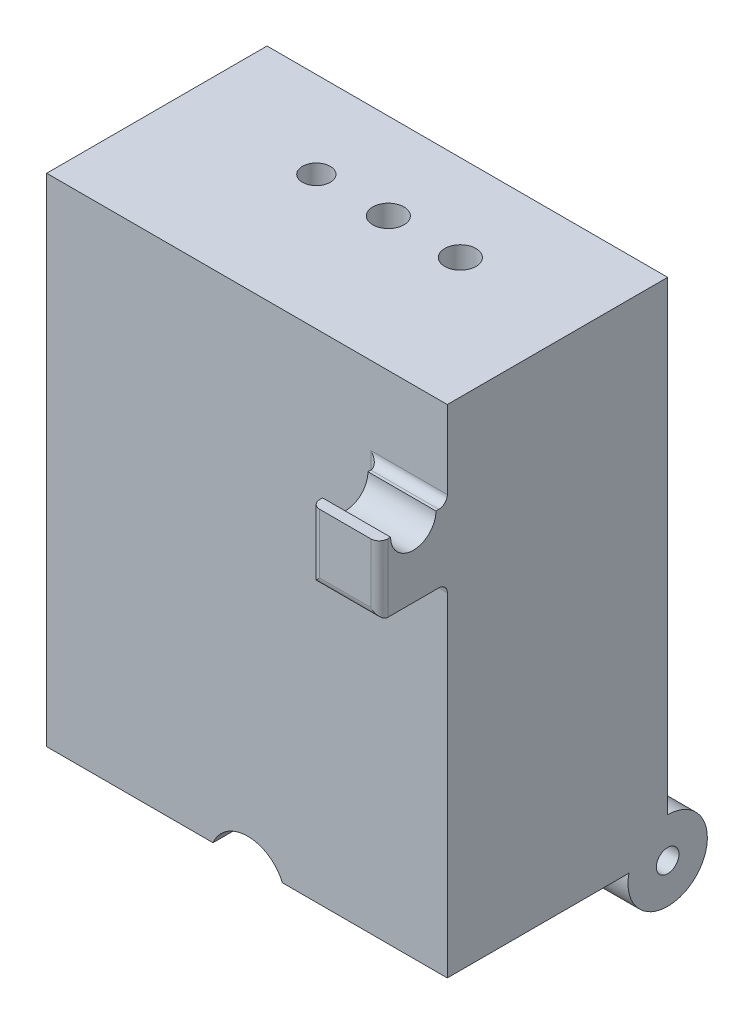
SolidWorks part; units mm, degrees
ref_plane "Front Plane" through (0, 0, 0) normal (0, 0, 1) x (1, 0, 0)
ref_plane "Top Plane" through (0, 0, 0) normal (0, 1, 0) x (1, 0, 0)
ref_plane "Right Plane" through (0, 0, 0) normal (1, 0, 0) x (0, 0, -1)
sketch "Sketch1" plane through (0, 0, 0) normal (1, 0, 0) x (0, 0, -1)
  line L1 (-15.935, -35.8) -> (15.935, -35.8)
  line L2 (-15.935, -35.8) -> (-15.935, 35.8)
  line L3 (-15.935, 35.8) -> (15.935, 35.8)
  line L4 (15.935, -35.8) -> (15.935, 35.8)
  line L5 (-15.935, -35.8) -> (15.935, 35.8) construction
  line L6 (-15.935, 35.8) -> (15.935, -35.8) construction
  point P0 (0, 0)
extrude "Boss-Extrude1" add sketch "Sketch1" along normal blind 56.17
sketch "Sketch2" plane through (0, 0, -15.935) normal (0, 0, -1) x (-1, 0, 0)
  line L4 (-56.17, 35.8) -> (-56.17, -35.8)
  line L5 (-56.17, -35.8) -> (0, -35.8)
  line L6 (0, -35.8) -> (0, 35.8)
  line L7 (0, 35.8) -> (-56.17, 35.8)
  line L8 (8, -43.8) -> (8, 43.8)
  line L9 (8, 43.8) -> (-64.17, 43.8)
  line L10 (-64.17, 43.8) -> (-64.17, -43.8)
  line L11 (-64.17, -43.8) -> (8, -43.8)
  line L12 (8, -43.8) -> (8, 43.8)
  line L13 (8, 43.8) -> (-64.17, 43.8)
  line L14 (-64.17, 43.8) -> (-64.17, -43.8)
  line L15 (-64.17, -43.8) -> (8, -43.8)
  line L16 (1, 36.8) -> (-57.17, 36.8)
  line L17 (-57.17, 36.8) -> (-57.17, -36.8)
  line L18 (-57.17, -36.8) -> (1, -36.8)
  line L19 (1, -36.8) -> (1, 36.8)
  dimension "D1" = 8
  dimension "D2" = 1
extrude "Boss-Extrude4" add sketch "Sketch2" along normal blind 31.87 separate body contours L14 L15 L12 L13 L19 L18 L17 L16
sketch "Sketch5" plane through (0, 0, -15.935) normal (0, 0, 1) x (1, 0, 0)
  line L0 (-8, 43.8) -> (64.17, 43.8)
  line L1 (64.17, 43.8) -> (64.17, -43.8)
  line L2 (64.17, -43.8) -> (-8, -43.8)
  line L3 (-8, -43.8) -> (-8, 43.8)
extrude "Boss-Extrude5" add sketch "Sketch5" along normal blind 7
sketch "Sketch6" plane through (0, 0, 0) normal (-1, 0, 0) x (0, 0, 1)
  line L0 (-8.935, 35.8) -> (15.935, 35.8)
  line L1 (15.935, 35.8) -> (15.935, -35.8)
  line L2 (15.935, -35.8) -> (-8.935, -35.8)
  line L3 (-8.935, -35.8) -> (-8.935, 35.8)
extrude "Cut-Extrude2" cut sketch "Sketch6" against normal through all
sketch "Sketch7" plane through (-8, 0, 0) normal (-1, 0, 0) x (0, 0, 1)
  line L0 (-8.935, -43.8) -> (-47.805, -43.8) construction
  circle A0 centre (-47.805, -45.3) radius 7
  dimension "D1" = 1.5
extrude "Boss-Extrude6" add sketch "Sketch7" against normal blind 20
sketch "Sketch8" plane through (64.17, 0, 0) normal (1, 0, 0) x (0, 0, -1)
  line L0 (8.935, -43.8) -> (47.805, -43.8) construction
  circle A0 centre (47.805, -45.3) radius 7
  dimension "D1" = 1.5
extrude "Boss-Extrude7" add sketch "Sketch8" against normal blind 20
sketch "Sketch9" plane through (0, 43.8, 0) normal (0, 1, 0) x (1, 0, 0)
  line L0 (-8, 8.935) -> (-8, 47.805) construction
  line L1 (-8, 47.805) -> (64.17, 47.805) construction
  circle A0 centre (41.35, 32.555) radius 2.753
  circle A1 centre (28.65, 32.555) radius 2.75
  circle A2 centre (15.95, 32.555) radius 2.45
  dimension "D1" = 12.7
  dimension "D2" = 12.7
  dimension "D3" = 23.95
  dimension "D4" = 15.25
  dimension "D5" = 15.25
  dimension "D6" = 15.25
extrude "Cut-Extrude3" cut sketch "Sketch9" against normal blind 20
sketch "Sketch10" plane through (0, 0, -47.805) normal (0, 0, -1) x (-1, 0, 0)
  line L0 (-44.17, -43.8) -> (-12, -43.8) construction
  line L1 (-33.5678, -43.8) -> (-21.3444, -43.8)
  arc A1 (-33.5678, -43.8) -> (-21.3444, -43.8) centre (-27.4561, -46.3689) cw
extrude "Cut-Extrude4" cut sketch "Sketch10" against normal blind 40
sketch "Sketch11" plane through (-8, 0, 0) normal (-1, 0, 0) x (0, 0, 1)
  line L0 (-8.935, -43.8) -> (-40.9676, -43.8) construction
  line L1 (-25.2846, -26.7914) -> (-43.7481, -26.7914)
  line L2 (-25.2846, -26.7914) -> (-25.2846, -11.8)
  line L3 (-25.2846, -11.8) -> (-43.7481, -11.8)
  line L4 (-43.7481, -26.7914) -> (-43.7481, -11.8)
  line L5 (-25.2846, -26.7914) -> (-43.7481, -11.8) construction
  line L6 (-25.2846, -11.8) -> (-43.7481, -26.7914) construction
  point P0 (-34.5163, -19.2957)
  dimension "D1" = 32
extrude "Cut-Extrude5" cut sketch "Sketch11" against normal blind 10
sketch "Sketch12" plane through (-8, 0, 0) normal (-1, 0, 0) x (0, 0, 1)
  circle A0 centre (-47.805, -45.3) radius 2
extrude "Cut-Extrude6" cut sketch "Sketch12" against normal through all
sketch "Sketch13" plane through (0, 43.8, 0) normal (0, 1, 0) x (1, 0, 0)
  line L1 (64.17, 8.935) -> (62.67, 8.935)
  line L2 (64.17, 8.935) -> (64.17, 58.1895)
  line L3 (64.17, 58.1895) -> (62.67, 58.1895)
  line L4 (62.67, 8.935) -> (62.67, 58.1895)
extrude "Cut-Extrude7" cut sketch "Sketch13" against normal through all
sketch "Sketch14" plane through (0, 0, -8.935) normal (0, 0, 1) x (1, 0, 0)
  line L0 (62.67, -43.8) -> (62.67, 43.8) construction
  line L1 (62.67, 28.5411) -> (50.67, 28.5411)
  line L2 (62.67, 28.5411) -> (62.67, 16.5411)
  line L3 (62.67, 16.5411) -> (50.67, 16.5411)
  line L4 (50.67, 28.5411) -> (50.67, 16.5411)
extrude "Boss-Extrude8" add sketch "Sketch14" along normal blind 12
sketch "Sketch15" plane through (62.67, 0, 0) normal (1, 0, 0) x (0, 0, -1)
  line L0 (-3.065, 28.5411) -> (8.935, 28.5411) construction
  circle A0 centre (2.935, 28.5411) radius 4
extrude "Cut-Extrude8" cut sketch "Sketch15" against normal blind 12
fillet "Fillet1" radius 1.5 6 edges at (62.67, 22.5411, 3.065) (50.67, 22.5411, 3.065) (56.67, 16.5411, 3.065) (56.67, 28.5411, -8.935) (50.67, 22.5411, -8.935) (56.67, 16.5411, -8.935)
